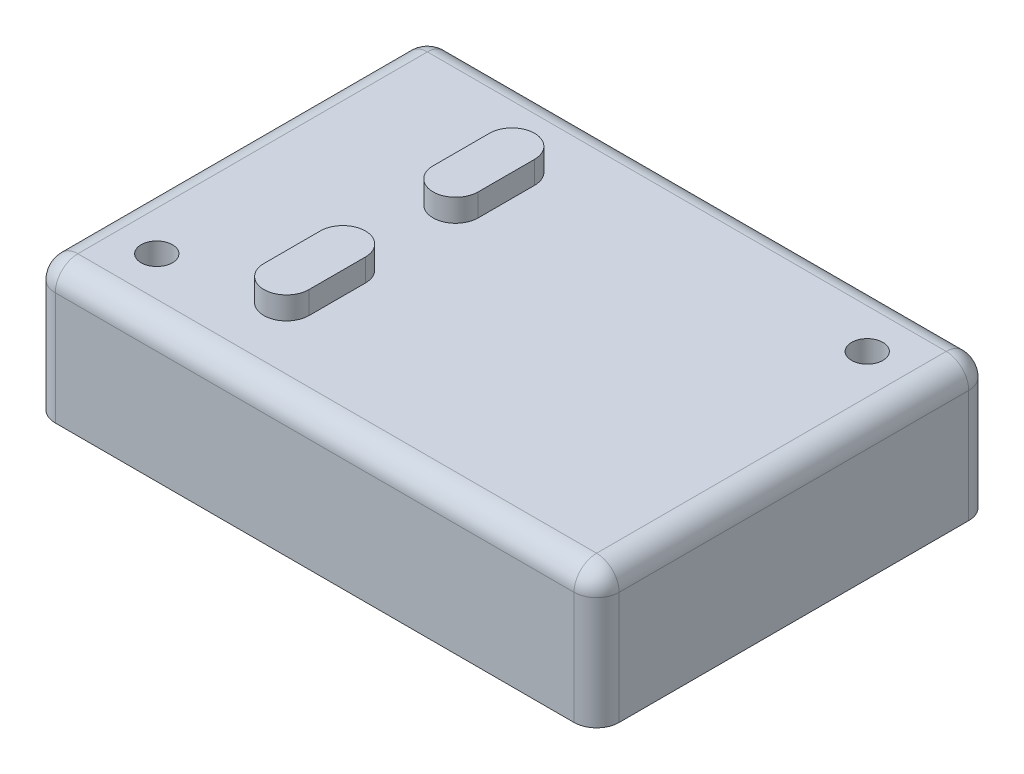
SolidWorks part; units mm, degrees
ref_plane "Front Plane" through (0, 0, 0) normal (0, 0, 1) x (1, 0, 0)
ref_plane "Top Plane" through (0, 0, 0) normal (0, 1, 0) x (1, 0, 0)
ref_plane "Right Plane" through (0, 0, 0) normal (1, 0, 0) x (0, 0, -1)
sketch "Sketch1" plane through (0, 0, 0) normal (0, 1, 0) x (1, 0, 0)
  line L1 (-25, -17.5) -> (25, -17.5)
  line L2 (-25, -17.5) -> (-25, 17.5)
  line L3 (-25, 17.5) -> (25, 17.5)
  line L4 (25, -17.5) -> (25, 17.5)
  line L5 (-25, -17.5) -> (25, 17.5) construction
  line L6 (-25, 17.5) -> (25, -17.5) construction
  point P0 (0, 0)
  dimension "D1" = 50
  dimension "D2" = 35
extrude "Boss-Extrude1" add sketch "Sketch1" along normal blind 12
sketch "Sketch2" plane through (0, 12, 0) normal (0, 1, 0) x (1, 0, 0)
  line L0 (-10, 10) -> (-10, 5) construction
  line L1 (-8, 10) -> (-8, 5)
  line L2 (-12, 10) -> (-12, 5)
  line L3 (-10, -5) -> (-10, -10) construction
  line L4 (-8, -5) -> (-8, -10)
  line L5 (-12, -5) -> (-12, -10)
  arc A0 (-8, 10) -> (-12, 10) centre (-10, 10) ccw
  arc A1 (-12, 5) -> (-8, 5) centre (-10, 5) ccw
  arc A2 (-8, -5) -> (-12, -5) centre (-10, -5) ccw
  arc A3 (-12, -10) -> (-8, -10) centre (-10, -10) ccw
  point P2 (-10, 7.5)
  point P7 (-10, -7.5)
  dimension "D3" = 2
  dimension "D1" = 15
  dimension "D2" = 7.5
  dimension "D4" = 5
  dimension "D5" = 10
extrude "Boss-Extrude2" add sketch "Sketch2" along normal blind 2
fillet "Fillet1" radius 2 8 edges at (-25, 12, 0) (0, 12, -17.5) (-25, 6, -17.5) (25, 12, 0) (25, 6, -17.5) (-25, 6, 17.5) (0, 12, 17.5) (25, 6, 17.5)
sketch "Sketch4" plane through (0, 0, 0) normal (0, -1, 0) x (1, 0, 0)
  line L1 (25, 15.5) -> (25, -15.5) construction
  line L2 (-25, -15.5) -> (-25, 15.5) construction
  line L4 (-23, 17.5) -> (23, 17.5) construction
  line L5 (23, -17.5) -> (-23, -17.5) construction
  circle A0 centre (-19.5, 12) radius 1.39
  circle A1 centre (19.5, -12) radius 1.39
  dimension "D1" = 2.78
  dimension "D2" = 5.5
  dimension "D3" = 5.5
  dimension "D4" = 5.5
  dimension "D5" = 5.5
extrude "Cut-Extrude1" cut sketch "Sketch4" against normal through all
equation "\"D2@Sketch2\"=\"D1@Sketch2\"/2"
